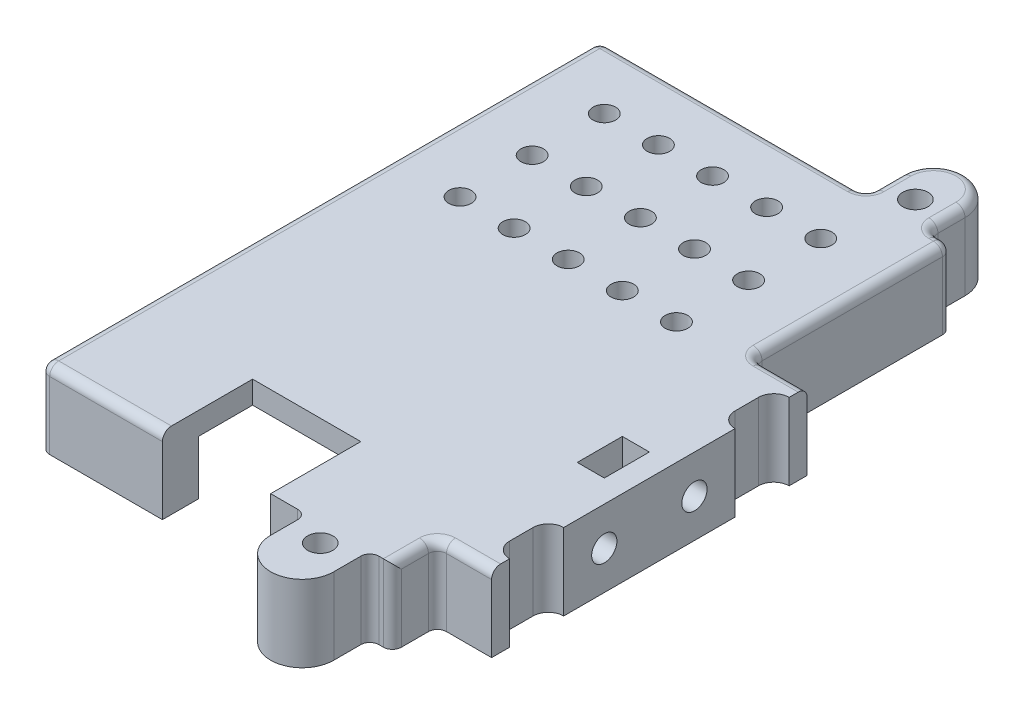
SolidWorks part; units mm, degrees
ref_plane "Front Plane" through (0, 0, 0) normal (0, 0, 1) x (1, 0, 0)
ref_plane "Top Plane" through (0, 0, 0) normal (0, 1, 0) x (1, 0, 0)
ref_plane "Right Plane" through (0, 0, 0) normal (1, 0, 0) x (0, 0, -1)
sketch "Sketch1" plane through (0, 0, 0) normal (0, 1, 0) x (1, 0, 0)
  line L0 (-14.5, -26) -> (14.5, -26) construction
  line L1 (-14.5, -26) -> (-14.5, 26) construction
  line L2 (-14.5, 26) -> (14.5, 26) construction
  line L3 (14.5, -26) -> (14.5, 26) construction
  line L4 (0, 26) -> (0, -26) construction
  line L6 (-15.5, 27) -> (15.5, 27)
  line L7 (-15.5, 27) -> (-15.5, -27)
  line L8 (-15.5, -27) -> (15.5, -27)
  line L9 (15.5, 27) -> (15.5, -27)
  line L10 (-19.5, 31) -> (19.5, 31)
  line L11 (-19.5, 31) -> (-19.5, -31)
  line L12 (-19.5, -31) -> (19.5, -31)
  line L13 (19.5, 31) -> (19.5, -31)
  point P6 (0, 0)
  point P16 (0, 31)
  point P17 (-15.5, 0)
  point P18 (-19.5, 0)
  dimension "D1" = 52
  dimension "D2" = 29
  dimension "D3" = 1
  dimension "D4" = 1
  dimension "D5" = 1
  dimension "D6" = 1
  dimension "D7" = 4
  dimension "D8" = 4
extrude "Base" add sketch "Sketch1" along normal blind 6
sketch "Sketch2" plane through (0, 6, 0) normal (0, 1, 0) x (1, 0, 0)
  line L0 (0, 31) -> (0, -31) construction
  line L1 (-19.5, 31) -> (19.5, 31)
  line L2 (-19.5, 31) -> (-19.5, -31)
  line L3 (-19.5, -31) -> (19.5, -31)
  line L4 (19.5, 31) -> (19.5, -31)
  circle A0 centre (-12, 24) radius 1.25
  circle A1 centre (-6, 24) radius 1.25
  circle A2 centre (0, 24) radius 1.25
  circle A3 centre (6, 24) radius 1.25
  circle A4 centre (12, 24) radius 1.25
  circle A5 centre (-6, 16) radius 1.25
  circle A6 centre (0, 16) radius 1.25
  circle A7 centre (6, 16) radius 1.25
  circle A8 centre (12, 16) radius 1.25
  circle A9 centre (-6, 8) radius 1.25
  circle A10 centre (0, 8) radius 1.25
  circle A11 centre (6, 8) radius 1.25
  circle A12 centre (12, 8) radius 1.25
  circle A13 centre (-12, 16) radius 1.25
  circle A14 centre (-12, 8) radius 1.25
  dimension "D1" = 2.5
  dimension "D2" = 12
  dimension "D3" = 7
  dimension "D6" = 6
  dimension "D7" = 8
  dimension "D4" = 5
  dimension "D5" = 3
extrude "Top Cover" add sketch "Sketch2" along normal blind 2.5
sketch "Sketch3" plane through (0, 0, 0) normal (0, 1, 0) x (1, 0, 0)
  line L0 (10, 31) -> (17, 31)
  line L1 (19.5, 31) -> (-19.5, 31) construction
  line L2 (-19.5, 0) -> (19.5, 0) construction
  line L3 (-19.5, 31) -> (-19.5, -31) construction
  line L4 (19.5, -31) -> (19.5, 31) construction
  line L5 (10, 31) -> (10, 35)
  line L6 (17, 31) -> (17, 35)
  line L7 (10, -31) -> (10, -35)
  line L8 (10, -31) -> (17, -31)
  line L9 (17, -31) -> (17, -35)
  circle A0 centre (13.5, 33) radius 1.4
  arc A1 (10, 35) -> (17, 35) centre (13.5, 35) cw
  circle A2 centre (13.5, -33) radius 1.4
  arc A3 (10, -35) -> (17, -35) centre (13.5, -35) ccw
  point P10 (13.5, 31)
  dimension "D2" = 33
  dimension "D3" = 2.8
  dimension "D4" = 4
  dimension "D1" = 7
  dimension "D5" = 13.5
extrude "Mounting Ends" add sketch "Sketch3" along normal up to surface (8.5 mm away) up to face at (-12, 8.5, -14.75)
sketch "Sketch5" plane through (0, 0, 0) normal (0, 1, 0) x (1, 0, 0)
  line L0 (19.5, -26) -> (25.5, -26)
  line L1 (19.5, -31) -> (19.5, 31) construction
  line L3 (25.5, 9) -> (19.5, 9)
  line L4 (17, -31) -> (19.5, -31) construction
  line L5 (25.5, -26) -> (25.5, -24)
  line L6 (25.5, -18) -> (25.5, 1)
  line L7 (23.8, -19.7) -> (23.8, -22.3)
  line L8 (25.5, 9) -> (25.5, 7)
  line L9 (23.8, 2.7) -> (23.8, 5.3)
  line L10 (19.5, 9) -> (19.5, -26)
  arc A0 (23.8, -22.3) -> (25.5, -24) centre (25.5, -22.3) ccw
  arc A1 (23.8, -19.7) -> (25.5, -18) centre (25.5, -19.7) cw
  arc A2 (23.8, 2.7) -> (25.5, 1) centre (25.5, 2.7) ccw
  arc A3 (23.8, 5.3) -> (25.5, 7) centre (25.5, 5.3) cw
  point P21 (23.8, 4)
  point P22 (23.8, -21)
  dimension "D4" = 1.7
  dimension "D1" = 6
  dimension "D2" = 5
  dimension "D3" = 35
  dimension "D5" = 6
  dimension "D6" = 2.6
  dimension "D7" = 2.6
  dimension "D8" = 25
  dimension "D9" = 2
extrude "Basket Mounting Edge" add sketch "Sketch5" along normal up to surface (8.5 mm away) up to face at (-12, 8.5, -14.75)
sketch "Sketch6" plane through (25.5, 0, 0) normal (1, 0, 0) x (0, 0, -1)
  line L0 (-18, 4.25) -> (1, 4.25) construction
  line L1 (-18, 8.5) -> (-18, 0) construction
  line L2 (1, 8.5) -> (1, 0) construction
  line L3 (-8.5, 8.5) -> (-8.5, 0) construction
  line L4 (-18, 8.5) -> (1, 8.5) construction
  line L5 (-18, 0) -> (1, 0) construction
  circle A0 centre (-13.5, 4.25) radius 1.4
  circle A1 centre (-3.5, 4.25) radius 1.4
  dimension "D1" = 2.8
  dimension "D2" = 4.5
extrude "Basket Clamp Screw Holes" cut sketch "Sketch6" against normal blind 8
sketch "Sketch8" plane through (0, 0, 31) normal (0, 0, 1) x (1, 0, 0)
  line L5 (-19.5, 0) -> (10, 0) construction
  line L6 (-6, 0) -> (6, 0)
  line L7 (-6, 0) -> (-6, 8.5)
  line L8 (-6, 8.5) -> (6, 8.5)
  line L9 (6, 0) -> (6, 8.5)
  line L10 (-19.5, 8.5) -> (10, 8.5) construction
  dimension "D1" = 12
extrude "USB Opening" cut sketch "Sketch8" against normal blind 10
fillet "1mm Edge Fillets" radius 1 18 edges at (19.5, 8.5, -20) (19.5, 4.25, -9) (19.5, 4.25, 26) (22.5, 8.5, -9) (22.5, 8.5, 26) (-19.5, 8.5, 0) (19.5, 8.5, 28.5) (18.25, 8.5, -31) (-4.75, 8.5, -31) (17, 4.25, -31) (10, 4.25, -31) (13.5, 8.5, -38.5) (-19.5, 4.25, -31) (19.5, 4.25, -31) (19.5, 4.25, 31) (-19.5, 4.25, 31) (10, 4.25, 31) (17, 4.25, 31)
sketch "Sketch7" plane through (0, 8.5, 0) normal (0, 1, 0) x (1, 0, 0)
  line L0 (25.5, -18) -> (25.5, 1) construction
  line L1 (20, -6) -> (23, -6)
  line L2 (20, -6) -> (20, -11)
  line L3 (20, -11) -> (23, -11)
  line L4 (23, -6) -> (23, -11)
  point P6 (25.5, -8.5)
  point P7 (23, -8.5)
  dimension "D1" = 2.5
  dimension "D2" = 3
  dimension "D3" = 5
extrude "Zip Tie Hole" cut sketch "Sketch7" against normal through all
